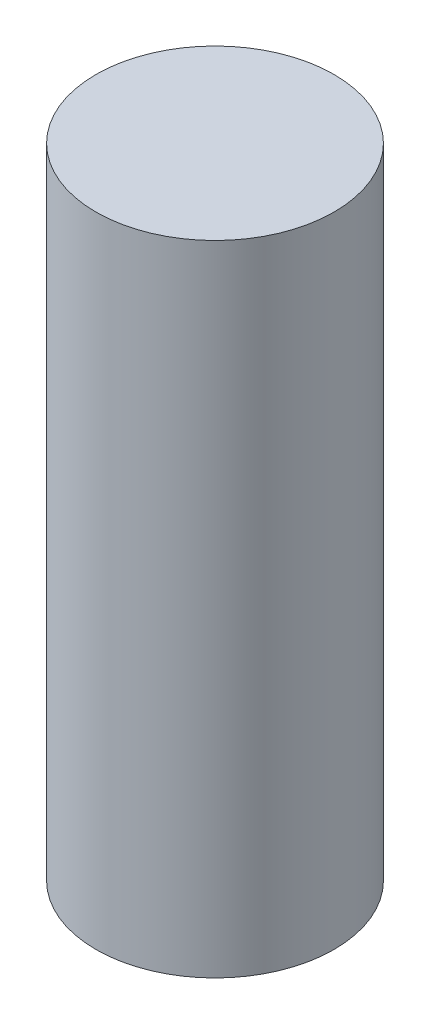
SolidWorks part; units mm, degrees
ref_plane "Front Plane" through (0, 0, 0) normal (0, 0, 1) x (1, 0, 0)
ref_plane "Top Plane" through (0, 0, 0) normal (0, 1, 0) x (1, 0, 0)
ref_plane "Right Plane" through (0, 0, 0) normal (1, 0, 0) x (0, 0, -1)
sketch "Sketch1" plane through (0, 0, 0) normal (0, 1, 0) x (1, 0, 0)
  circle A0 centre (0, 0) radius 5.595
  dimension "D1" = 11.19
extrude "Boss-Extrude1" add sketch "Sketch1" along normal blind 30 contours A0
